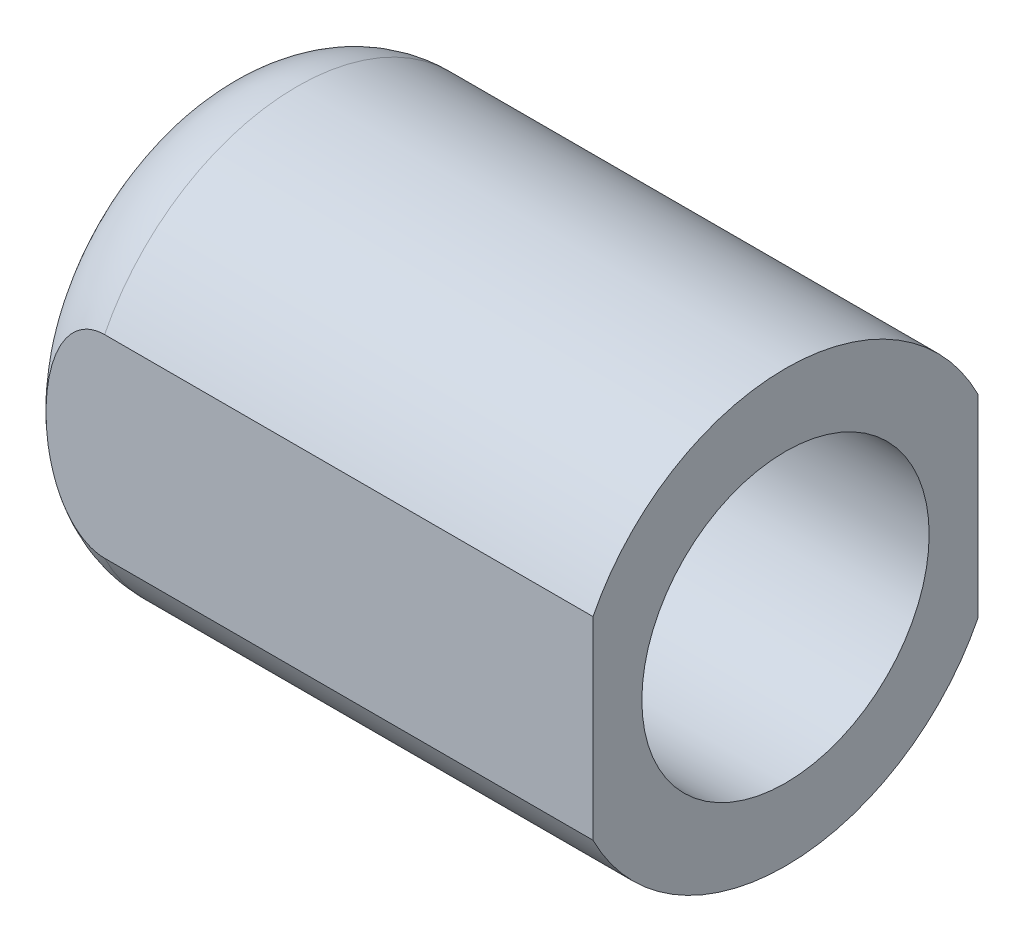
SolidWorks part; units mm, degrees
ref_plane "Front Plane" through (0, 0, 0) normal (0, 0, 1) x (1, 0, 0)
ref_plane "Top Plane" through (0, 0, 0) normal (0, 1, 0) x (1, 0, 0)
ref_plane "Right Plane" through (0, 0, 0) normal (1, 0, 0) x (0, 0, -1)
sketch "Sketch1" plane through (0, 0, 0) normal (0, 0, 1) x (1, 0, 0)
  line L0 (18, 7.5) -> (18, 5)
  line L1 (18, 5) -> (0, 5)
  line L2 (0, 5) -> (0, 0)
  line L3 (18, 7.5) -> (-2, 7.5)
  line L4 (-2, 7.5) -> (-2, 0)
  line L5 (-2, 0) -> (0, 0)
  dimension "D1" = 20
  dimension "D2" = 2
  dimension "D3" = 2.5
  dimension "D4" = 5
revolve "Revolve1" add sketch "Sketch1" angle 360 about L5
fillet "Fillet1" radius 3 1 edges at (-2, 0, 7.5)
sketch "Sketch2" plane through (18, 0, 0) normal (1, 0, 0) x (0, 0, -1)
  line L1 (6.7, -8.7294) -> (-6.7, -8.7294)
  line L2 (6.7, -8.7294) -> (6.7, 8.7294)
  line L3 (6.7, 8.7294) -> (-6.7, 8.7294)
  line L4 (-6.7, -8.7294) -> (-6.7, 8.7294)
  line L5 (6.7, -8.7294) -> (-6.7, 8.7294) construction
  line L6 (6.7, 8.7294) -> (-6.7, -8.7294) construction
  line L7 (-8.5968, -11.3574) -> (8.5968, -11.3574)
  line L8 (-8.5968, -11.3574) -> (-8.5968, 11.3574)
  line L9 (-8.5968, 11.3574) -> (8.5968, 11.3574)
  line L10 (8.5968, -11.3574) -> (8.5968, 11.3574)
  line L11 (-8.5968, -11.3574) -> (8.5968, 11.3574) construction
  line L12 (-8.5968, 11.3574) -> (8.5968, -11.3574) construction
  point P0 (0, 0)
  point P6 (0, 0)
  dimension "D1" = 6.7
extrude "Cut-Extrude1" cut sketch "Sketch2" against normal through all
sketch "Sketch3" plane through (0, 0, 0) normal (1, 0, 0) x (0, 0, -1)
  arc A0 (0.4896, 0.161) -> (-0.4896, 0.161) centre (0, 0.825) ccw
  arc A1 (-0.4896, -0.161) -> (0.4896, -0.161) centre (0, -0.825) ccw
  arc A2 (-0.4896, -0.161) -> (-0.4896, 0.161) centre (-0.6083, 0) ccw
  arc A3 (0.4896, -0.161) -> (0.4896, 0.161) centre (0.6083, 0) cw
  point P5 (0, 0)
  dimension "D1" = 1.65
  dimension "D2" = 0.825
  dimension "D4" = 0.2
  dimension "D5" = 0.2
  dimension "D3" = 2
extrude "Cut-Extrude3" cut sketch "Sketch3" against normal through all
